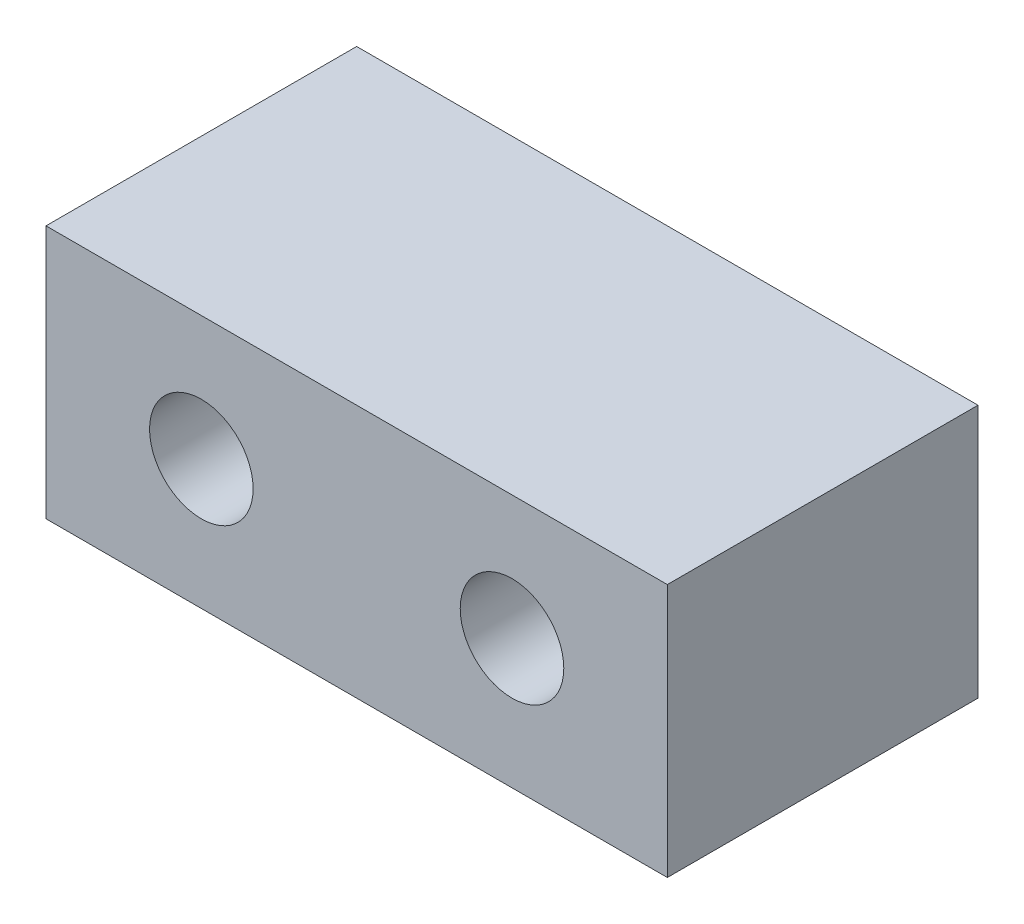
SolidWorks part; units mm, degrees
ref_plane "Ön Düzlem" through (0, 0, 0) normal (0, 0, 1) x (1, 0, 0)
ref_plane "Üst Düzlem" through (0, 0, 0) normal (0, 1, 0) x (1, 0, 0)
ref_plane "Sağ Düzlem" through (0, 0, 0) normal (1, 0, 0) x (0, 0, -1)
sketch "Sketch1" plane through (0, 0, 0) normal (0, 0, 1) x (1, 0, 0)
  line L0 (-15, 1.35) -> (15, 1.35) construction
  line L1 (-15, -7.35) -> (15, -7.35)
  line L2 (-15, -7.35) -> (-15, 7.35)
  line L3 (-15, 7.35) -> (15, 7.35)
  line L4 (15, -7.35) -> (15, 7.35)
  line L5 (-15, -7.35) -> (15, 7.35) construction
  line L6 (-15, 7.35) -> (15, -7.35) construction
  circle A0 centre (7.5, 1.35) radius 2.5
  circle A1 centre (-7.5, 1.35) radius 2.5
  point P0 (0, 0)
  dimension "D6" = 5
  dimension "D7" = 5
  dimension "D1" = 30
  dimension "D2" = 14.7
  dimension "D3" = 15
  dimension "D4" = 7.5
  dimension "D5" = 6
extrude "Boss-Extrude1" add sketch "Sketch1" along normal blind 15
sketch "Sketch4" plane through (0, 0, 0) normal (0, 0, -1) x (-1, 0, 0)
  circle A0 centre (-7.5, 1.35) radius 4.5
  circle A1 centre (7.5, 1.35) radius 4.5
  dimension "D1" = 9
  dimension "D2" = 9
extrude "Cut-Extrude1" cut sketch "Sketch4" against normal blind 6
sketch "Sketch6" plane through (0, 0, 0) normal (0, 0, -1) x (-1, 0, 0)
  line L0 (15, -7.35) -> (-15, -7.35) construction
  line L1 (-19.1805, -4.9) -> (24.6095, -4.9)
  line L2 (-19.1805, -4.9) -> (-19.1805, -13.1821)
  line L3 (-19.1805, -13.1821) -> (24.6095, -13.1821)
  line L4 (24.6095, -4.9) -> (24.6095, -13.1821)
  dimension "D1" = 2.45
extrude "Cut-Extrude2" cut sketch "Sketch6" against normal through all
